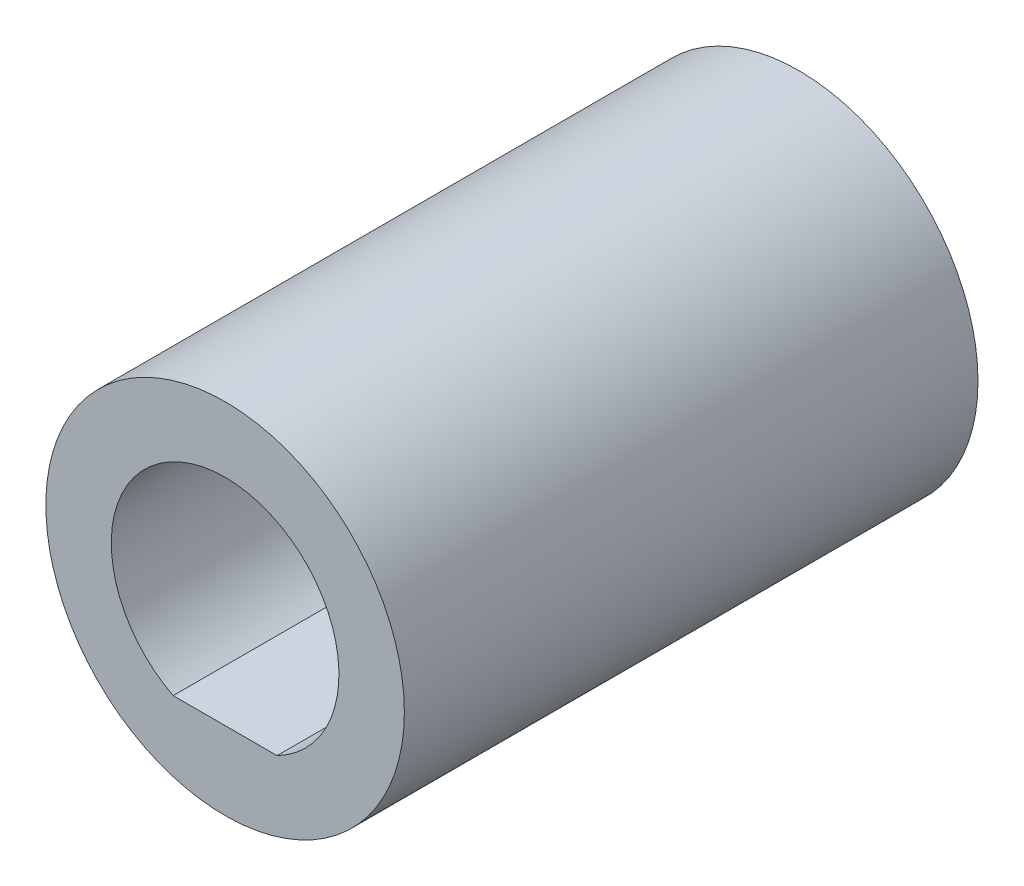
SolidWorks part; units mm, degrees
ref_plane "Front Plane" through (0, 0, 0) normal (0, 0, 1) x (1, 0, 0)
ref_plane "Top Plane" through (0, 0, 0) normal (0, 1, 0) x (1, 0, 0)
ref_plane "Right Plane" through (0, 0, 0) normal (1, 0, 0) x (0, 0, -1)
sketch "Sketch1" plane through (0, 0, 0) normal (0, 0, 1) x (1, 0, 0)
  line L0 (-0.7246, -1.4125) -> (0.7246, -1.4125)
  line L6 (0, -1.5875) -> (0, 1.5875)
  circle A2 centre (0, 0) radius 1.5875
  circle A3 centre (0, 0) radius 2.5
  dimension "D1" = 3.175
  dimension "D2" = 0.175
  dimension "D3" = 5
extrude "Boss-Extrude4" add sketch "Sketch1" along normal blind 8 contours L0 A2 L6 | L6 A2 L0 | A3 A2
